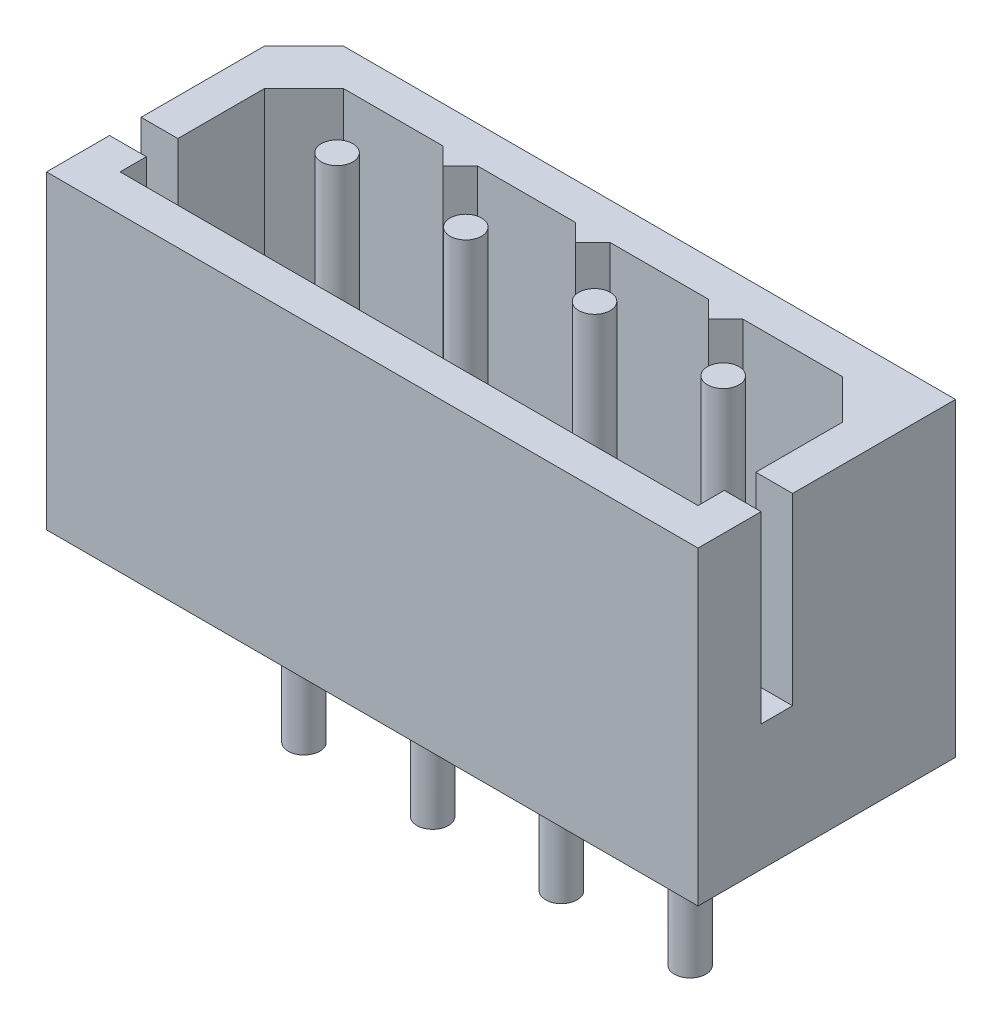
SolidWorks part; units mm, degrees
ref_plane "Front Plane" through (0, 0, 0) normal (0, 0, 1) x (1, 0, 0)
ref_plane "Top Plane" through (0, 0, 0) normal (0, 1, 0) x (1, 0, 0)
ref_plane "Right Plane" through (0, 0, 0) normal (1, 0, 0) x (0, 0, -1)
sketch "Sketch1" plane through (0, 0, 0) normal (0, 1, 0) x (1, 0, 0)
  line L0 (-5.45, 2.45) -> (-6.2, 1.7)
  line L1 (-5.45, 2.45) -> (6.2, 2.45)
  line L2 (-6.2, 1.7) -> (-6.2, -2.45)
  line L3 (-6.2, -2.45) -> (6.2, -2.45)
  line L4 (6.2, 2.45) -> (6.2, -2.45)
  line L5 (-6.2, 2.45) -> (6.2, -2.45) construction
  line L6 (-6.2, -2.45) -> (6.2, 2.45) construction
  point P0 (0, 0)
  dimension "D1" = 4.9
  dimension "D2" = 12.4
extrude "Boss-Extrude1" add sketch "Sketch1" against normal blind 5.9
sketch "Sketch2" plane through (0, -5.9, 0) normal (0, -1, 0) x (1, 0, 0)
  line L0 (-6.2, 0) -> (6.2, 0) construction
  line L1 (-6.2, -1.7) -> (-6.2, 2.45) construction
  line L2 (6.2, 2.45) -> (6.2, -2.45) construction
  line L3 (0, 2.45) -> (0, -2.45) construction
  line L4 (-6.2, 2.45) -> (6.2, 2.45) construction
  line L5 (6.2, -2.45) -> (-5.45, -2.45) construction
  line L6 (-3.75, 0) -> (-1.3, 0) construction
  line L7 (-6.2, -1.7) -> (-6.2, 2.45) construction
  line L8 (6.2, -2.45) -> (-5.45, -2.45) construction
  circle A0 centre (-3.75, 0) radius 0.3
  circle A1 centre (-1.3, 0) radius 0.3
  circle A2 centre (1.15, 0) radius 0.3
  circle A3 centre (3.6, 0) radius 0.3
  dimension "D1" = 0.6
  dimension "D2" = 2.45
  dimension "D5" = 2.45
  dimension "D4" = 2.45
  dimension "D3" = 4
extrude "Boss-Extrude2" add sketch "Sketch2" along normal blind 3.5
sketch "Sketch3" plane through (0, 0, 0) normal (0, 1, 0) x (1, 0, 0)
  line L0 (-6.2, -2.45) -> (6.2, -2.45) construction
  line L1 (-4.75, 1.75) -> (4.75, 1.75)
  line L2 (-5.5, 1) -> (-5.5, -0.65)
  line L3 (-5.5, -1.75) -> (5.5, -1.75)
  line L4 (5.5, 1) -> (5.5, -0.65)
  line L5 (-5.5, 1.75) -> (5.5, -1.75) construction
  line L6 (-5.5, -1.75) -> (5.5, 1.75) construction
  line L7 (-5.5, 0.63) -> (5.5, 0.63) construction
  line L8 (-3.75, 0.63) -> (-1.3, 0.63) construction
  line L9 (-2.525, 1.75) -> (-2.525, -1.75) construction
  line L10 (-2.525, 1.4218) -> (-2.8532, 1.75)
  line L11 (-2.525, 1.4218) -> (-2.1968, 1.75)
  line L13 (0, 1.4218) -> (-0.3282, 1.75)
  line L14 (0, 1.4218) -> (0.3282, 1.75)
  line L15 (2.525, 1.4218) -> (2.1968, 1.75)
  line L16 (2.525, 1.4218) -> (2.8532, 1.75)
  line L17 (6.2, -0.65) -> (5.5, -0.65)
  line L18 (-4.75, 1.75) -> (-5.5, 1)
  line L19 (4.75, 1.75) -> (5.5, 1)
  line L20 (-5.5, -1.25) -> (-6.2, -1.25)
  line L21 (-6.2, 1.7) -> (-6.2, -2.45) construction
  line L22 (-6.2, -1.25) -> (-6.2, -0.65)
  line L23 (-6.2, -0.65) -> (-5.5, -0.65)
  line L24 (-5.5, -1.25) -> (-5.5, -1.75)
  line L25 (0, -1.75) -> (0, 1.75) construction
  line L26 (6.2, -1.25) -> (6.2, -0.65)
  line L27 (5.5, -1.25) -> (6.2, -1.25)
  line L28 (5.5, -1.25) -> (5.5, -1.75)
  circle A0 centre (-3.75, 0.63) radius 0.3
  circle A1 centre (-1.3, 0.63) radius 0.3
  circle A2 centre (1.15, 0.63) radius 0.3
  circle A3 centre (3.6, 0.63) radius 0.3
  point P0 (0, 0)
  line M11 (6.2, -2.45) -> (6.2, 2.45)
  line M14 (-6.2, 1.7) -> (-6.2, -2.45)
  dimension "D4" = 1.75
  dimension "D5" = 0.6
  dimension "D8" = 2.975
  dimension "D1" = 11
  dimension "D2" = 0.7
  dimension "D3" = 2.38
  dimension "D7" = 2.45
  dimension "D9" = 45
  dimension "D10" = 45
  dimension "D11" = 0.6565
  dimension "D14" = 0.6
  dimension "D15" = 0.5
  dimension "D6" = 4
  dimension "D12" = 3
extrude "Cut-Extrude1" cut sketch "Sketch3" against normal blind 3.5 contours L28 L27 L17 L4 L19 L1 L16 L15 L14 L13 L11 L10 L18 L2 L23 L20 L24 L3 A3 A2 A1 A0 M11 M14
